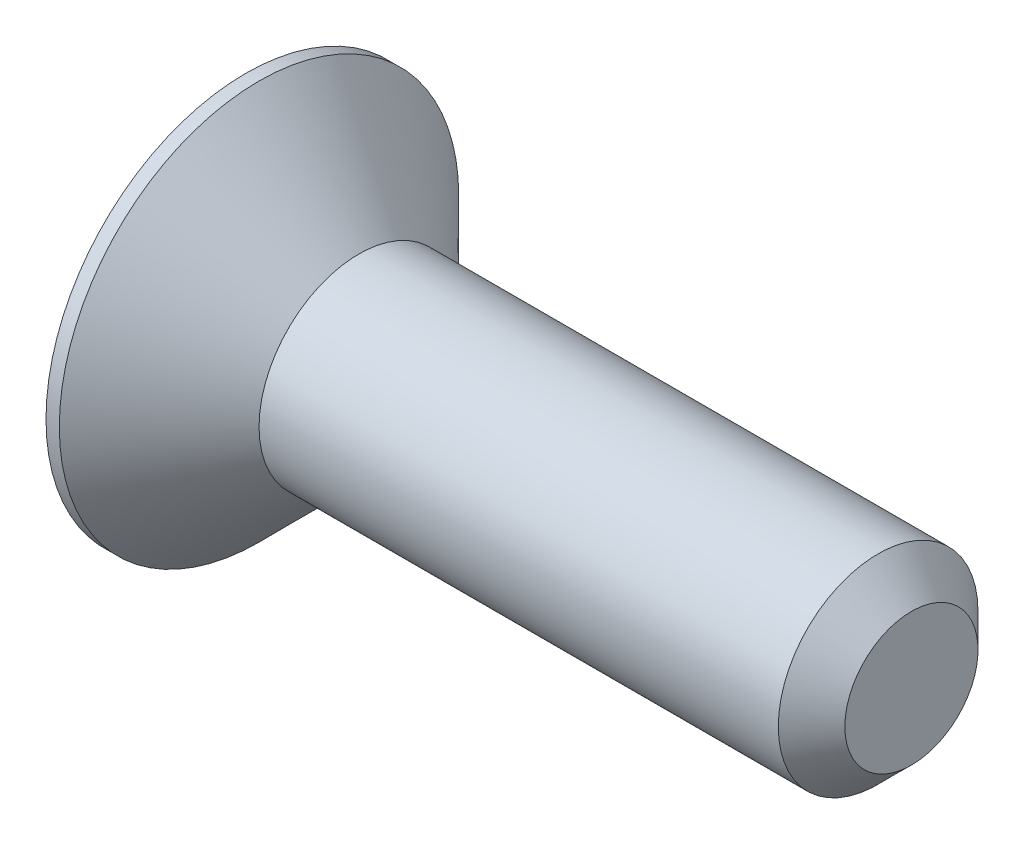
SolidWorks part; units mm, degrees
material "SUS304相当"
ref_plane "Front Plane" through (0, 0, 0) normal (0, 0, 1) x (1, 0, 0)
ref_plane "Top Plane" through (0, 0, 0) normal (0, 1, 0) x (1, 0, 0)
ref_plane "Right Plane" through (0, 0, 0) normal (1, 0, 0) x (0, 0, -1)
sketch "Sketch1" plane through (0, 0, 0) normal (0, 0, 1) x (1, 0, 0)
  line L0 (-1.7, 0) -> (8.3, 0) construction
  line L2 (0, -1.5) -> (7.8, -1.5)
  line L4 (-1.7, -3) -> (-1.5, -3)
  line L5 (8.3, -1) -> (8.3, 0)
  line L6 (-1.7, -3) -> (-1.7, 0)
  line L7 (-1.7, 0) -> (8.3, 0)
  line L9 (-1.5, -3) -> (0, -1.5)
  line L11 (7.8, -1.5) -> (8.3, -1)
  line L12 (8.3, 1) -> (7.8, 1.5) construction
  point P8 (-1.7, -3.36)
  point P12 (-1.7, 3.36)
  point P13 (7.8, -1.5)
  point P14 (-1.7, 3)
  dimension "L" = 10
  dimension "D1" = 45
  dimension "M" = 3
  dimension "Pitch" = 0.5
  dimension "BLT_3" = 0.5
  dimension "D2" = 45
  dimension "BLT_1" = 6.72
  dimension "E" = 1.7
  dimension "A" = 6
revolve "Revolve1" add sketch "Sketch1" angle 360 about L0
cosmetic thread "Thread1"
sketch "Sketch2" plane through (-1.7, 0, 0) normal (-1, 0, 0) x (0, 0, 1)
  line L1 (0, 1.1547) -> (-1, 0.5774)
  line L2 (-1, 0.5774) -> (-1, -0.5774)
  line L3 (-1, -0.5774) -> (0, -1.1547)
  line L4 (0, -1.1547) -> (1, -0.5774)
  line L5 (1, -0.5774) -> (1, 0.5774)
  line L6 (1, 0.5774) -> (0, 1.1547)
  circle A0 centre (0, 0) radius 1 construction
  dimension "B" = 2
extrude "Cut-Extrude1" cut sketch "Sketch2" against normal blind 1.1
equation "\"Pitch\"= iif ( \"M\" = 10 , 1.5 , iif ( \"M\" = 8 , 1.25 , iif ( \"M\" = 6 , 1 , iif ( \"M\" = 5 , 0.8 , iif ( \"M\" = 4 , 0.7 , iif ( \"M\" = 3 , 0.5 , iif ( \"M\" = 2.5 , 0.45 , 0.4 ) ) ) ) ) ) )"
equation "\"Factor\"= 1.082532"
equation "\"ATD_1\"= round ( \"M\" - \"Factor\" * \"Pitch\" , 3 )"
equation "\"BLT_3@Sketch1\"= \"Pitch\""
